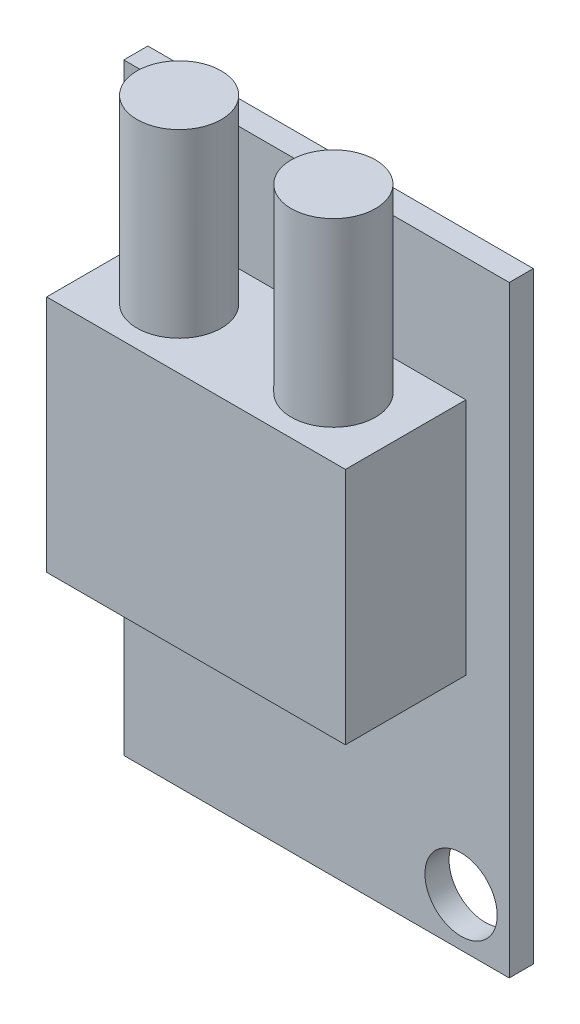
SolidWorks part; units mm, degrees
ref_plane "Ebene vorne" through (0, 0, 0) normal (0, 0, 1) x (1, 0, 0)
ref_plane "Ebene oben" through (0, 0, 0) normal (0, 1, 0) x (1, 0, 0)
ref_plane "Ebene rechts" through (0, 0, 0) normal (1, 0, 0) x (0, 0, -1)
sketch "Sketch1" plane through (0, 0, 0) normal (0, 0, 1) x (1, 0, 0)
  line L1 (0, 0) -> (16, 0)
  line L2 (0, 0) -> (0, 25)
  line L3 (0, 25) -> (16, 25)
  line L4 (16, 0) -> (16, 25)
  dimension "D1" = 16
  dimension "D2" = 25
extrude "Boss-Extrude1" add sketch "Sketch1" along normal blind 1
sketch "Sketch2" plane through (0, 0, 1) normal (0, 0, 1) x (1, 0, 0)
  line L0 (16, 25) -> (0, 25) construction
  line L1 (16, 0) -> (16, 25) construction
  line L2 (0, 25) -> (0, 0) construction
  line L3 (0, 0) -> (16, 0) construction
  circle A0 centre (2, 23) radius 1.5
  circle A1 centre (14, 2) radius 1.5
  point P4 (2.2019, 22.9314)
  point P9 (0, 19.3076)
  dimension "D1" = 3
  dimension "D2" = 2
  dimension "D5" = 2
  dimension "D3" = 2
  dimension "D4" = 2
extrude "Cut-Extrude1" cut sketch "Sketch2" against normal blind 1
sketch "Sketch3" plane through (0, 0, 1) normal (0, 0, 1) x (1, 0, 0)
  line L0 (8, 0) -> (8, 25) construction
  line L1 (1.8, 19.8816) -> (14.2, 19.8816)
  line L2 (1.8, 19.8816) -> (1.8, 9.9816)
  line L3 (1.8, 9.9816) -> (14.2, 9.9816)
  line L4 (14.2, 19.8816) -> (14.2, 9.9816)
  line L5 (0, 0) -> (16, 0) construction
  line L6 (16, 25) -> (0, 25) construction
  dimension "D1" = 9.9
  dimension "D2" = 12.4
extrude "Boss-Extrude2" add sketch "Sketch3" along normal blind 5
sketch "Sketch4" plane through (0, 19.8816, 0) normal (0, 1, 0) x (1, 0, 0)
  line L0 (1.8, -6) -> (1.8, -1) construction
  line L1 (14.2, -6) -> (14.2, -1) construction
  line L2 (1.8, -3.5) -> (14.2, -3.5) construction
  circle A0 centre (4.8, -3.5) radius 1.75
  circle A1 centre (11.2, -3.5) radius 1.75
  point P10 (0, 0)
  point P11 (0, 0)
  dimension "D1" = 3.5
  dimension "D2" = 3
  dimension "D3" = 3
extrude "Boss-Extrude3" add sketch "Sketch4" along normal blind 7.5
